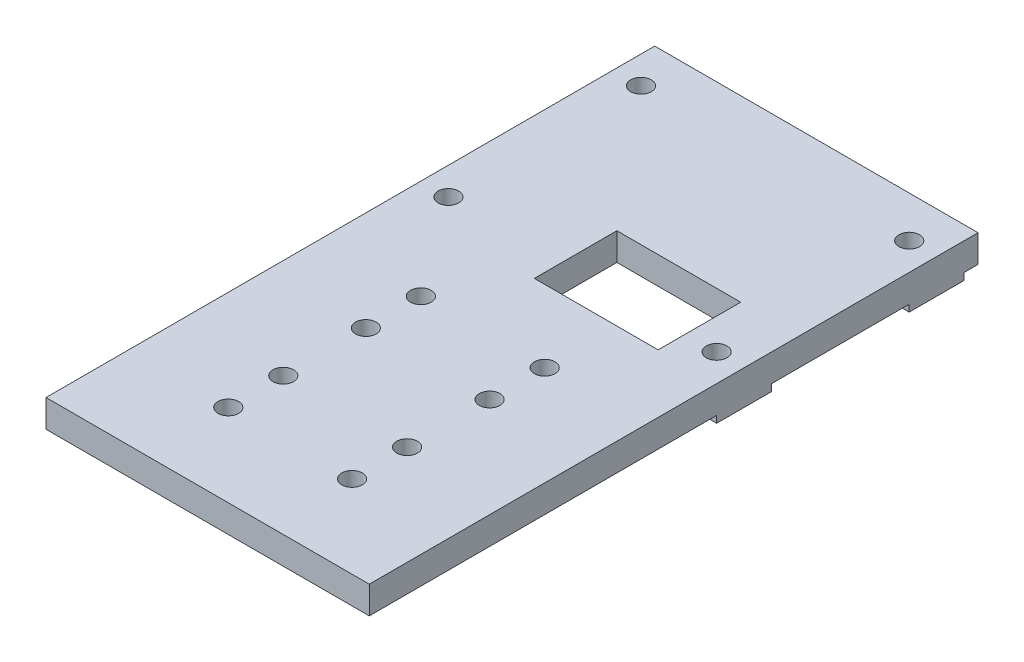
SolidWorks part; units mm, degrees
material "聚脂树脂"
ref_plane "前视基准面" through (0, 0, 0) normal (0, 0, 1) x (1, 0, 0)
ref_plane "上视基准面" through (0, 0, 0) normal (0, 1, 0) x (1, 0, 0)
ref_plane "右视基准面" through (0, 0, 0) normal (1, 0, 0) x (0, 0, -1)
other "Configuration Table"
sketch "草图1" plane through (0, 0, 0) normal (0, 1, 0) x (1, 0, 0)
  line L0 (0, 0) -> (0, 40.9092) construction
  line L1 (-23.5, -20) -> (23.5, -20)
  line L2 (-23.5, -20) -> (-23.5, 20)
  line L3 (-23.5, 20) -> (23.5, 20)
  line L4 (23.5, -20) -> (23.5, 20)
  line L5 (-23.5, -20) -> (23.5, 20) construction
  line L6 (-23.5, 20) -> (23.5, -20) construction
  line L7 (0, 0) -> (66.2179, 0) construction
  line L16 (0, 0) -> (0, -21.1131) construction
  line L17 (-15, -6) -> (15, -6)
  line L18 (15, -6) -> (15, -18)
  line L19 (15, -18) -> (-15, -18)
  line L20 (-15, -6) -> (-15, -18)
  line L21 (-23.5, -20) -> (-23.5, -73.5)
  line L22 (-23.5, -73.5) -> (23.5, -73.5)
  line L23 (23.5, -73.5) -> (23.5, -20)
  line L24 (0, -6) -> (0, -18)
  line L25 (-3, -6) -> (-3, -18)
  circle A0 centre (19.5, 14) radius 1.5
  circle A1 centre (19.5, -14) radius 1.5
  circle A2 centre (-19.5, -14) radius 1.5
  circle A3 centre (-19.5, 14) radius 1.5
  point P0 (0, 0)
  point P23 (0, -18)
  point P24 (0, -6)
  dimension "D3" = 3
  dimension "D4" = 39
  dimension "D5" = 28
  dimension "D1" = 47
  dimension "D2" = 40
  dimension "D6" = 30
  dimension "D7" = 12
  dimension "D8" = 6
  dimension "D9" = 73.5
  dimension "D10" = 3
extrude "凸台-拉伸1" add sketch "草图1" along normal blind 4 contours L1 L4 L3 L2 A1 A0 L20 L17 L18 L19 A2 A3 | L22 L23 L1 L21 | L24 L17 L20 L19
sketch "草图3" plane through (0, 0, 0) normal (0, -1, 0) x (1, 0, 0)
  line L0 (0, 0) -> (41.6004, 0) construction
  line L5 (15.5, -18) -> (23.5, -18)
  line L6 (15.5, 10) -> (23.5, 10)
  line L7 (0, 0) -> (0, 32.2448) construction
  line L16 (15.5, 10) -> (15.5, 18)
  line L17 (15.5, 18) -> (23.5, 18)
  line L22 (23.5, 10) -> (23.5, 18)
  line L23 (15.5, 10) -> (23.5, 18) construction
  line L24 (15.5, 18) -> (23.5, 10) construction
  line L25 (23.5, -10) -> (23.5, -18)
  line L26 (15.5, -10) -> (23.5, -10)
  line L27 (15.5, -10) -> (15.5, -18)
  line L28 (-15.5, -10) -> (-15.5, -18)
  line L29 (-15.5, -10) -> (-23.5, -10)
  line L30 (-23.5, -10) -> (-23.5, -18)
  line L31 (-15.5, -18) -> (-23.5, -18)
  line L32 (-15.5, 18) -> (-23.5, 18)
  line L33 (-23.5, 10) -> (-23.5, 18)
  line L34 (-15.5, 10) -> (-23.5, 10)
  line L35 (-15.5, 10) -> (-15.5, 18)
  circle A8 centre (-19.5, 14) radius 1.5 construction
  circle A9 centre (-19.5, -14) radius 1.5 construction
  circle A10 centre (19.5, -14) radius 1.5 construction
  circle A11 centre (19.5, 14) radius 1.5 construction
  circle A12 centre (-19.5, 14) radius 1.5
  circle A13 centre (-19.5, -14) radius 1.5
  circle A14 centre (19.5, -14) radius 1.5
  circle A15 centre (19.5, 14) radius 1.5
  point P0 (19.5, 14)
  point P22 (-19.5, 14)
  dimension "D1" = 8
  dimension "D2" = 8
extrude "凸台-拉伸2" add sketch "草图3" along normal blind 1
sketch "草图4" plane through (0, 4, 0) normal (0, 1, 0) x (1, 0, 0)
  line L0 (0, 0) -> (0, -68.5) construction
  line L1 (-23.5, -73.5) -> (23.5, -73.5) construction
  line L2 (-23.5, -68.5) -> (23.5, -68.5)
  line L3 (-23.5, -73.5) -> (-23.5, 20) construction
  line L4 (23.5, -73.5) -> (23.5, 20) construction
  line L5 (23.5, -68.5) -> (23.5, -73.5)
  line L6 (23.5, -73.5) -> (-23.5, -73.5)
  line L7 (-23.5, -73.5) -> (-23.5, -68.5)
  circle A0 centre (9, -28.5) radius 1.5
  circle A1 centre (9, -48.5) radius 1.5
  circle A2 centre (-9, -48.5) radius 1.5
  circle A3 centre (-9, -28.5) radius 1.5
  circle A4 centre (-9, -36.5) radius 1.5
  circle A5 centre (9, -36.5) radius 1.5
  circle A6 centre (9, -56.5) radius 1.5
  circle A7 centre (-9, -56.5) radius 1.5
  dimension "D1" = 3
  dimension "D2" = 3
  dimension "D3" = 20
  dimension "D4" = 18
  dimension "D5" = 25
  dimension "D6" = 18
  dimension "D9" = 8
  dimension "D7" = 5
  dimension "D8" = 2
extrude "切除-拉伸2" cut sketch "草图4" against normal blind 4
sketch "草图5" plane through (0, 4, 0) normal (0, 1, 0) x (1, 0, 0)
  line L0 (0, -5) -> (0, 34.0121) construction
  line L1 (0, -5) -> (39.4094, -5) construction
  line L2 (15, -5) -> (23.5, -5)
  line L3 (23.5, -68.5) -> (23.5, 20) construction
  line L4 (23.5, -5) -> (23.5, -9)
  line L5 (23.5, -9) -> (15, -9)
  line L6 (15, -9) -> (15, -5)
  line L7 (-23.5, -9) -> (-15, -9)
  line L8 (-23.5, -5) -> (-23.5, -9)
  line L9 (-15, -5) -> (-23.5, -5)
  line L10 (-15, -9) -> (-15, -5)
  line L11 (0, 0) -> (38.2779, 0) construction
  line L12 (0, 0) -> (0, 10.5962) construction
  dimension "D1" = 30
  dimension "D2" = 5
  dimension "D3" = 4
